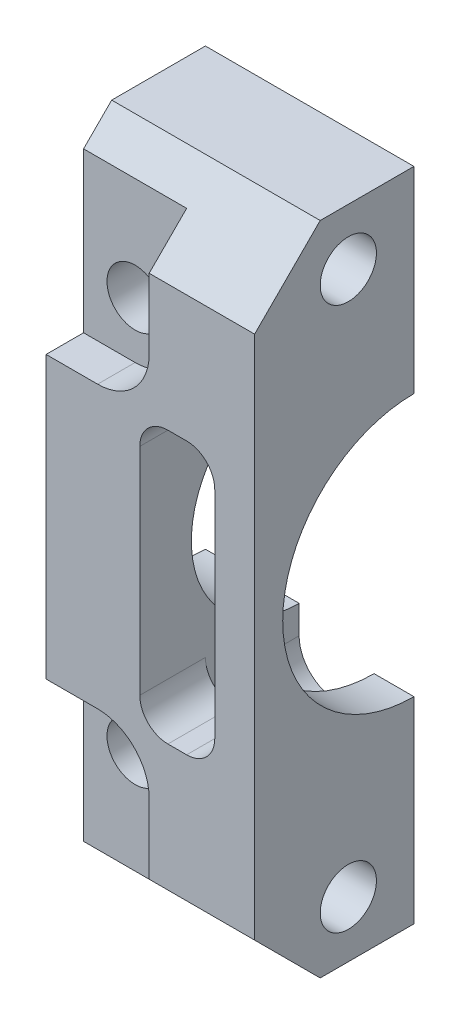
SolidWorks part; units mm, degrees
material "AISI 304"
ref_plane "Front Plane" through (0, 0, 0) normal (0, 0, 1) x (1, 0, 0)
ref_plane "Top Plane" through (0, 0, 0) normal (0, 1, 0) x (1, 0, 0)
ref_plane "Right Plane" through (0, 0, 0) normal (1, 0, 0) x (0, 0, -1)
sketch "Sketch1" plane through (0, 0, 0) normal (1, 0, 0) x (0, 0, -1)
  line L0 (0, 11.5) -> (0, 35)
  line L1 (0, -11.5) -> (0, -35)
  line L2 (0, -35) -> (-25, -35)
  line L3 (-25, -35) -> (-25, 35)
  line L4 (-25, 35) -> (0, 35)
  arc A0 (0, 11.5) -> (0, -11.5) centre (0, 0) ccw
  dimension "D1" = 23
  dimension "D2" = 70
  dimension "D3" = 25
extrude "Boss-Extrude1" add sketch "Sketch1" along normal blind 10
sketch "Sketch2" plane through (10, 0, 0) normal (1, 0, 0) x (0, 0, -1)
  line L0 (0, -14) -> (0, -35)
  line L1 (0, -35) -> (-25, -35)
  line L2 (-25, -35) -> (-25, 35)
  line L3 (-25, 35) -> (0, 35)
  line L4 (0, 35) -> (0, 14)
  arc A0 (0, 14) -> (0, -14) centre (0, 0) ccw
  dimension "D1" = 28
extrude "Boss-Extrude2" add sketch "Sketch2" along normal blind 12.25
sketch "Sketch3" plane through (0, -35, 0) normal (0, -1, 0) x (1, 0, 0)
  line L0 (22.25, 25) -> (22.25, 0) construction
  line L1 (0, 25) -> (22.25, 25)
  line L2 (0, 25) -> (0, 17)
  line L3 (0, 17) -> (22.25, 17)
  line L4 (22.25, 25) -> (22.25, 17)
  dimension "D1" = 8
extrude "Cut-Extrude1" cut sketch "Sketch3" against normal blind 80
sketch "Sketch8" plane through (22.25, 0, 0) normal (1, 0, 0) x (0, 0, -1)
  line L0 (-17, -35) -> (0, -35) construction
  line L1 (-17, -35) -> (-17, 35) construction
  line L2 (0, 35) -> (-17, 35) construction
  circle A0 centre (-7, -29) radius 3
  circle A1 centre (-7, 29) radius 3
  dimension "D1" = 6
  dimension "D2" = 6
  dimension "D3" = 10
  dimension "D4" = 6
  dimension "D6" = 6
  dimension "D5" = 10
extrude "Cut-Extrude4" cut sketch "Sketch8" against normal blind 25
sketch "Sketch6" plane through (0, 0, 0) normal (0, 0, -1) x (-1, 0, 0)
  line L0 (-10, 11.5) -> (-10, -11.5) construction
  line L2 (-18, -14.5) -> (-18, 14.5)
  line L4 (-10, -14.5) -> (-10, 14.5)
  line L7 (-10, -11.5) -> (0, -11.5) construction
  line L8 (-10, 11.5) -> (0, 11.5) construction
  arc A0 (-18, -14.5) -> (-10, -14.5) centre (-14, -14.5) ccw
  arc A1 (-10, 14.5) -> (-18, 14.5) centre (-14, 14.5) ccw
  point P7 (-14, -18.5)
  point P11 (-14, 18.5)
  dimension "D1" = 7
  dimension "D2" = 7
  dimension "D3" = 8
extrude "Cut-Extrude2" cut sketch "Sketch6" against normal blind 10
sketch "Sketch7" plane through (0, 0, 10) normal (0, 0, -1) x (-1, 0, 0)
  line L0 (-18, -9.798) -> (-18, -14.5) construction
  line L1 (-18, -14.5) -> (-10, -14.5)
  line L2 (-18, -14.5) -> (-18, 14.5)
  line L3 (-18, 14.5) -> (-10, 14.5)
  line L4 (-10, -14.5) -> (-10, 14.5)
  line L5 (-10, 11.5) -> (-10, 14.5) construction
  line L6 (-10, -11.5) -> (0, -11.5) construction
  line L7 (-10, 11.5) -> (0, 11.5) construction
  dimension "D1" = 3
  dimension "D2" = 3
extrude "Cut-Extrude3" cut sketch "Sketch7" against normal blind 10
fillet "Fillet1" radius 3 4 edges at (18, 14.5, 13.5) (10, 14.5, 13.5) (10, -14.5, 13.5) (18, -14.5, 13.5)
sketch "Sketch19" plane through (0, 0, 0) normal (0, 0, -1) x (-1, 0, 0)
  line L0 (0, -35) -> (0, -11.5) construction
  line L1 (-22.25, -35) -> (0, -35) construction
  line L2 (-22.25, 35) -> (0, 35) construction
  circle A0 centre (-5.5, -21) radius 3
  circle A1 centre (-5.5, 21) radius 3
  dimension "D1" = 6
  dimension "D2" = 6
  dimension "D3" = 5.5
  dimension "D4" = 14
  dimension "D5" = 14
extrude "Cut-Extrude5" cut sketch "Sketch19" against normal blind 20
ref_plane "Plane1" through (10, -14.5, 10) normal (0, 0, -1) x (-1, 0, 0)
sketch "Sketch21" plane through (0, 0, 0) normal (-1, 0, 0) x (0, 0, 1)
  line L1 (17, -35) -> (13, -35)
  line L2 (17, -35) -> (17, -15)
  line L3 (17, -15) -> (13, -15)
  line L4 (13, -35) -> (13, -15)
  line L5 (17, 35) -> (13, 35)
  line L6 (17, 35) -> (17, 15)
  line L7 (17, 15) -> (13, 15)
  line L8 (13, 35) -> (13, 15)
  dimension "D1" = 4
  dimension "D2" = 4
  dimension "D3" = 20
  dimension "D4" = 20
extrude "Cut-Extrude6" cut sketch "Sketch21" against normal blind 11
fillet "Fillet2" radius 5.5 2 edges at (11, -15, 15) (11, 15, 15)
chamfer "Chamfer1" distance 7 angle 45 2 edges at (16.625, -35, 17) (16.625, 35, 17)
